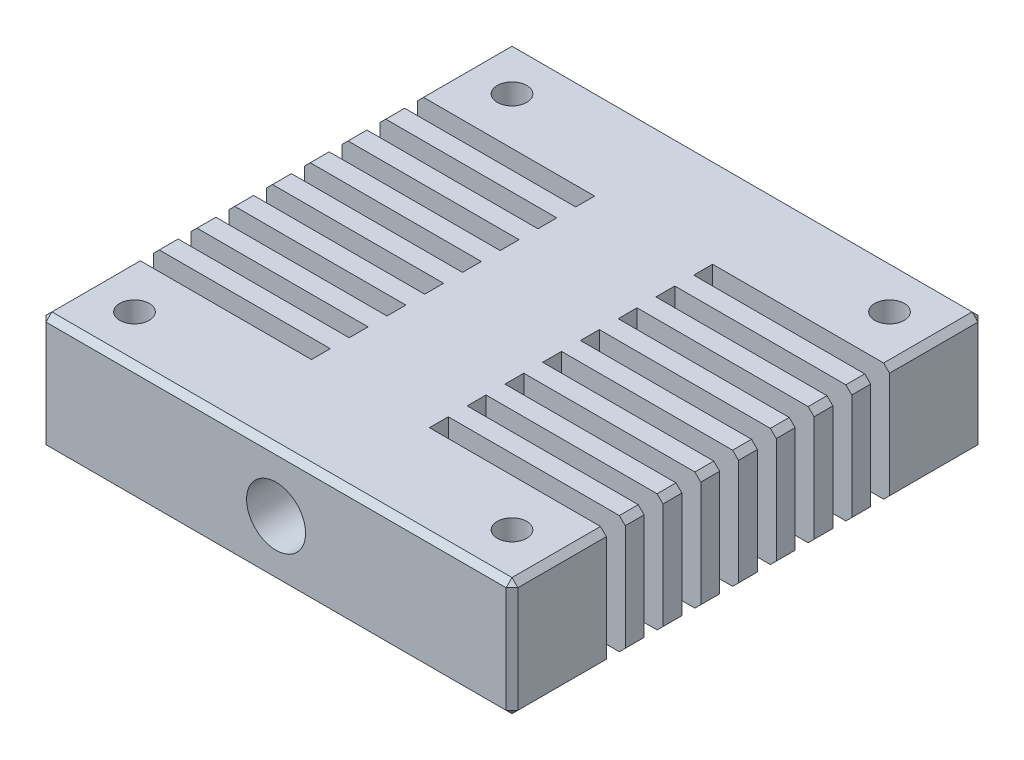
SolidWorks part; units mm, degrees
ref_plane "Plan de face" through (0, 0, 0) normal (0, 0, 1) x (1, 0, 0)
ref_plane "Plan de dessus" through (0, 0, 0) normal (0, 1, 0) x (1, 0, 0)
ref_plane "Plan de droite" through (0, 0, 0) normal (1, 0, 0) x (0, 0, -1)
sketch "Esquisse2" plane through (0, 0, 0) normal (0, 0, 1) x (1, 0, 0)
  line L1 (0, 0) -> (40, 0)
  line L2 (0, 0) -> (0, 10)
  line L3 (0, 10) -> (40, 10)
  line L4 (40, 0) -> (40, 10)
  dimension "D1" = 10
  dimension "D2" = 40
extrude "Boss.-Extru.1" add sketch "Esquisse2" along normal blind 40
sketch "Esquisse5" plane through (0, 0, 40) normal (0, 0, 1) x (1, 0, 0)
  line L0 (40, 0) -> (40, 10) construction
  line L1 (40, 10) -> (0, 10) construction
  circle A0 centre (20, 5) radius 2
  dimension "D1" = 4
  dimension "D2" = 20
  dimension "D3" = 5
hole_wizard "Diamètre du perçage Ø4.1 (4.1)1" positions "Esquisse7" profile "Esquisse6" hole size "Ø4.1" standard "ISO" end condition through all
sketch "Esquisse7" plane through (0, 0, 40) normal (0, 0, 1) x (1, 0, 0)
  point P0 (20, 5)
sketch "Esquisse6" plane through (20, 5, 40) normal (1, 0, 0) x (0, -1, 0)
  line L0 (0, 0) -> (0, 40)
  line L1 (0, 40) -> (2.05, 40)
  line L2 (2.05, 40) -> (2.05, 0)
  line L5 (2.05, 0) -> (0, 0)
  line L11 (0, -6.35) -> (0, 107.95) construction
  dimension "Diamètre du perçage jusqu'au prochain" = 4.1
  dimension "Profondeur du perçage jusqu'au prochain" = 40
hole_wizard "Trou pour taraudage pour trou taraudé M61" positions "Esquisse10" profile "Esquisse9" hole size "M6" standard "ISO"
sketch "Esquisse10" plane through (0, 0, 40) normal (0, 0, 1) x (1, 0, 0)
  point P0 (20, 5)
sketch "Esquisse9" plane through (20, 5, 40) normal (1, 0, 0) x (0, -1, 0)
  line L0 (0, 0) -> (0, 9.5022)
  line L1 (0, 9.5022) -> (2.5, 8)
  line L2 (2.5, 8) -> (2.5, 0)
  line L5 (2.5, 0) -> (0, 0)
  line L10 (0, 9.5022) -> (-2.5, 8) construction
  line L11 (0, -6.35) -> (0, 107.95) construction
  dimension "Diamètre du perçage" = 5
  dimension "Profondeur du perçage" = 8
  dimension "Angle de pointe" = 118
hole_wizard "Diamètre du perçage Ø6.0 (6)1" positions "Esquisse14" profile "Esquisse13" hole size "Ø6.0" standard "ISO"
sketch "Esquisse14" plane through (0, 0, 0) normal (0, 0, -1) x (-1, 0, 0)
  point P0 (-20, 5)
sketch "Esquisse13" plane through (20, 5, 0) normal (1, 0, 0) x (0, 1, 0)
  line L0 (0, 0) -> (0, 21.8026)
  line L1 (0, 21.8026) -> (3, 20)
  line L2 (3, 20) -> (3, 0)
  line L5 (3, 0) -> (0, 0)
  line L10 (0, 21.8026) -> (-3, 20) construction
  line L11 (0, -6.35) -> (0, 107.95) construction
  dimension "Diamètre du perçage" = 6
  dimension "Profondeur du perçage" = 20
  dimension "Angle de pointe" = 118
sketch "Esquisse15" plane through (0, 0, 0) normal (0, -1, 0) x (1, 0, 0)
  line L0 (0, 40) -> (40, 40) construction
  line L1 (0, 40) -> (0, 0) construction
  line L2 (40, 40) -> (40, 0) construction
  line L3 (0, 0) -> (40, 0) construction
  circle A0 centre (4, 36) radius 1.5
  circle A1 centre (36, 36) radius 1.5
  circle A2 centre (36, 4) radius 1.5
  circle A3 centre (4, 4) radius 1.5
  circle A4 centre (20, 4) radius 1.5
  dimension "D1" = 3
  dimension "D2" = 3
  dimension "D3" = 3
  dimension "D4" = 3
  dimension "D5" = 3
  dimension "D14" = 4
  dimension "D6" = 4
  dimension "D7" = 4
  dimension "D8" = 4
  dimension "D9" = 4
  dimension "D10" = 4
  dimension "D11" = 4
  dimension "D12" = 4
  dimension "D13" = 4
  dimension "D15" = 20
hole_wizard "Trou pour taraudage pour trou taraudé M32" positions "Esquisse17" profile "Esquisse16" hole size "M3" standard "ISO" end condition through all
sketch "Esquisse17" plane through (0, 0, 0) normal (0, -1, 0) x (-1, 0, 0)
  point P0 (-4, -36)
  point P3 (-36, -36)
  point P6 (-36, -4)
  point P9 (-4, -4)
sketch "Esquisse16" plane through (4, 0, 36) normal (1, 0, 0) x (0, 0, -1)
  line L0 (0, 0) -> (0, 10)
  line L1 (0, 10) -> (1.25, 10)
  line L2 (1.25, 10) -> (1.25, 0)
  line L5 (1.25, 0) -> (0, 0)
  line L11 (0, -6.35) -> (0, 107.95) construction
  dimension "Diamètre du perçage jusqu'au prochain" = 2.5
  dimension "Profondeur du perçage jusqu'au prochain" = 10
hole_wizard "Trou pour taraudage pour trou taraudé M31" positions "Esquisse19" profile "Esquisse18" hole size "M3" standard "ISO"
sketch "Esquisse19" plane through (0, 0, 0) normal (0, -1, 0) x (-1, 0, 0)
  point P0 (-20, -4)
sketch "Esquisse18" plane through (20, 0, 4) normal (1, 0, 0) x (0, 0, -1)
  line L0 (0, 0) -> (0, 5.7511)
  line L1 (0, 5.7511) -> (1.25, 5)
  line L2 (1.25, 5) -> (1.25, 0)
  line L5 (1.25, 0) -> (0, 0)
  line L10 (0, 5.7511) -> (-1.25, 5) construction
  line L11 (0, -6.35) -> (0, 107.95) construction
  dimension "Diamètre du perçage" = 2.5
  dimension "Profondeur du perçage" = 5
  dimension "Angle de pointe" = 118
chamfer "Chanfrein1" distance 0.5 angle 45 12 edges at (40, 5, 0) (20, 10, 0) (0, 5, 0) (20, 0, 0) (40, 10, 20) (40, 0, 20) (0, 10, 20) (0, 0, 20) (0, 5, 40) (20, 10, 40) (40, 5, 40) (20, 0, 40)
sketch "Esquisse20" plane through (0, 0, 0) normal (0, -1, 0) x (-1, 0, 0)
  line L0 (0, -40) -> (0, 0) construction
  line L1 (0, -32) -> (-15, -32)
  line L2 (0, -32) -> (0, -30.4)
  line L3 (0, -30.4) -> (-15, -30.4)
  line L4 (-15, -32) -> (-15, -30.4)
  line L5 (0, -40) -> (-40, -40) construction
  line L6 (-40, -40) -> (-40, 0) construction
  line L7 (-40, -32) -> (-25, -32)
  line L8 (-40, -32) -> (-40, -30.4)
  line L9 (-40, -30.4) -> (-25, -30.4)
  line L10 (-25, -32) -> (-25, -30.4)
  dimension "D1" = 1.6
  dimension "D2" = 15
  dimension "D3" = 8
  dimension "D4" = 1.6
  dimension "D5" = 15
  dimension "D6" = 8
extrude "Enlèv. mat.-Extru.1" cut sketch "Esquisse20" against normal through all
pattern_linear "Répétition linéaire1" count 8 spacing 3.2 along (0, 0, -1) of "Enlèv. mat.-Extru.1"
